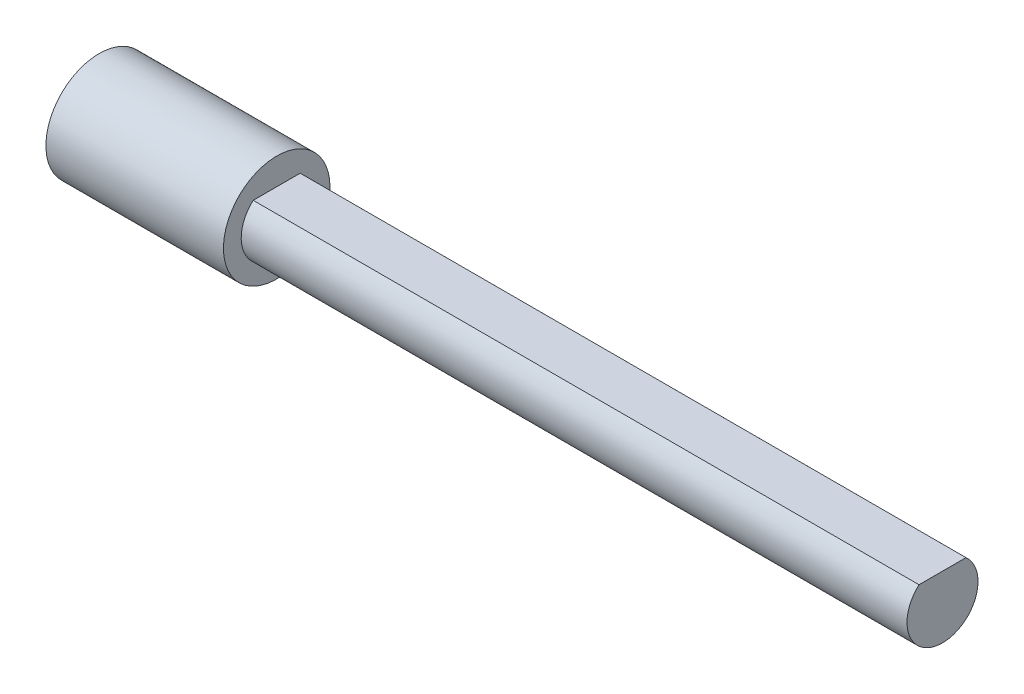
SolidWorks part; units mm, degrees
ref_plane "Front Plane" through (0, 0, 0) normal (0, 0, 1) x (1, 0, 0)
ref_plane "Top Plane" through (0, 0, 0) normal (0, 1, 0) x (1, 0, 0)
ref_plane "Right Plane" through (0, 0, 0) normal (1, 0, 0) x (0, 0, -1)
sketch "Sketch1" plane through (0, 0, 0) normal (1, 0, 0) x (0, 0, -1)
  circle A0 centre (0, 0) radius 6
  dimension "D1" = 12
extrude "Boss-Extrude1" add sketch "Sketch1" along normal blind 20
sketch "Sketch2" plane through (0, 0, 0) normal (-1, 0, 0) x (0, 0, 1)
  line L0 (-2.6833, 3.1) -> (2.6833, 3.1)
  line L1 (-2.6833, -3.1) -> (2.6833, -3.1)
  arc A0 (-2.6833, 3.1) -> (-2.6833, -3.1) centre (0, 0) ccw
  arc A1 (2.6833, -3.1) -> (2.6833, 3.1) centre (0, 0) ccw
  dimension "D1" = 8.2
  dimension "D2" = 6.2
  dimension "D3" = 3.1
extrude "Cut-Extrude1" cut sketch "Sketch2" against normal blind 15
sketch "Sketch3" plane through (20, 0, 0) normal (1, 0, 0) x (0, 0, -1)
  line L0 (2.6458, 3) -> (-2.6458, 3)
  arc A0 (-2.6458, 3) -> (2.6458, 3) centre (0, 0) ccw
  dimension "D1" = 8
  dimension "D2" = 3
extrude "Boss-Extrude2" add sketch "Sketch3" along normal blind 75
